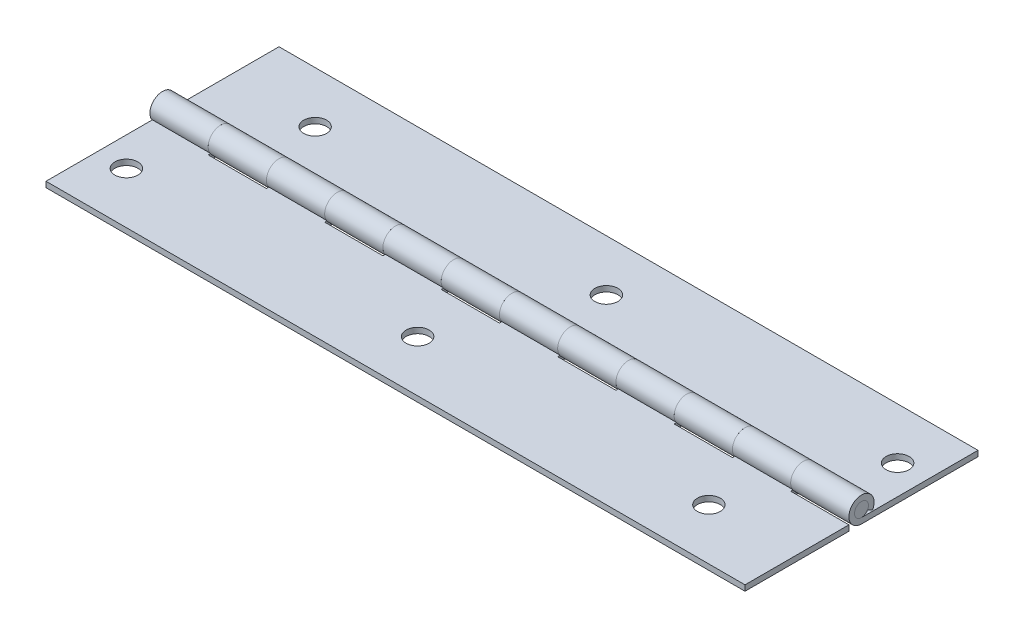
SolidWorks part; units mm, degrees
ref_plane "Front Plane" through (0, 0, 0) normal (0, 0, 1) x (1, 0, 0)
ref_plane "Top Plane" through (0, 0, 0) normal (0, 1, 0) x (1, 0, 0)
ref_plane "Right Plane" through (0, 0, 0) normal (1, 0, 0) x (0, 0, -1)
sketch "Sketch1" plane through (0, 0, 0) normal (0, 1, 0) x (1, 0, 0)
  line L0 (-76.2, 0) -> (76.2, 0) construction
  line L1 (-76.2, -25.4) -> (-76.2, 25.4) construction
  line L2 (-76.2, -25.4) -> (-69.85, -25.4) construction
  line L3 (-69.85, -25.4) -> (-6.35, -25.4) construction
  line L4 (-6.35, -25.4) -> (57.15, -25.4) construction
  line L5 (76.2, -25.4) -> (76.2, -14.224) construction
  line L6 (57.15, -25.4) -> (76.2, -25.4) construction
  line L7 (-76.2, 25.4) -> (-57.15, 25.4) construction
  line L8 (-57.15, 25.4) -> (6.35, 25.4) construction
  line L9 (6.35, 25.4) -> (69.85, 25.4) construction
  line L10 (69.85, 25.4) -> (76.2, 25.4) construction
  line L11 (57.15, -16.7259) -> (57.15, -11.7221) construction
  point P4 (0, 0)
  point P8 (-76.2, 0)
  point P17 (-63.5, 0)
  point P21 (57.15, -14.224)
  dimension "Leaf Height" = 152.4
  dimension "Overall Width" = 50.8
  dimension "Hole to End 1" = 6.35
  dimension "Hole Spacing" = 63.5
  dimension "D3" = 63.5
  dimension "Hole to End 2" = 19.05
  dimension "Hole Center to End" = 11.176
  dimension "D1" = 6.35
  dimension "D2" = 19.05
  dimension "D4" = 63.5
  dimension "D6" = 63.5
  dimension "Knuckle Length" = 12.7
  dimension "Hole Diameter" = 5.0038
sketch "Sketch2" plane through (0, 0, 0) normal (1, 0, 0) x (0, 0, -1)
  line L2 (0, -2.7432) -> (0, -1.524) construction
  line L4 (0, 1.524) -> (0, -1.524) construction
  point P8 (0, 0)
  dimension "Leaf Thickness" = 1.2192
  dimension "Pin Diameter" = 3.048
sketch "Sketch3" plane through (0, 0, 0) normal (1, 0, 0) x (0, 0, -1)
  line L3 (0, 0) -> (-2.7432, -1.524) construction
  line L4 (0, -2.7432) -> (-25.4, -2.7432)
  line L5 (-25.4, -2.7432) -> (-25.4, -1.524)
  line L7 (-25.4, -1.524) -> (0, -1.524)
  line L8 (-25.4, 0) -> (25.4, 0) construction
  line L9 (-1.3322, -0.7401) -> (-2.398, -1.3322)
  line L11 (-2.7432, 0) -> (-2.7432, -1.524) construction
  circle A4 centre (0, 0) radius 1.524 construction
  circle A5 centre (0, 0) radius 2.7432 construction
  arc A8 (-1.3322, -0.7401) -> (0, -1.524) centre (0, 0) cw
  arc A9 (-2.398, -1.3322) -> (0, -2.7432) centre (0, 0) cw
  point P0 (-2.398, -1.3322)
  point P13 (-1.3322, -0.7401)
extrude "Boss-Extrude1" add sketch "Sketch3" along normal mid plane 152.4
sketch "Sketch4" plane through (0, 0, 0) normal (0, 1, 0) x (1, 0, 0)
  line L0 (-76.2, -2.7432) -> (76.2, -2.7432) construction
  line L1 (-76.2, -2.7432) -> (76.2, -2.7432) construction
  line L2 (76.2, 2.7432) -> (-76.2, 2.7432) construction
  line L3 (76.2, 2.7432) -> (-76.2, 2.7432) construction
  line L4 (-63.5, -2.7432) -> (-63.5, 2.7432)
  line L6 (-63.5, 2.7432) -> (-50.8, 2.7432)
  line L7 (-50.8, -2.7432) -> (-63.5, -2.7432)
  line L8 (-50.8, 2.7432) -> (-50.8, -2.7432)
  point P8 (-63.5, 0)
  dimension "D1" = 12.7
extrude "Cut-Extrude1" cut sketch "Sketch4" against normal through all both and the other way through all
pattern_linear "LPattern1" count 6 spacing 25.4 along (1, 0, 0) of "Cut-Extrude1"
sketch "Sketch5" plane through (0, -1.524, 0) normal (0, 1, 0) x (1, 0, 0)
  line L0 (57.15, -14.224) -> (-69.85, -14.224) construction
  line L1 (-6.35, -14.224) -> (-6.35, -25.4) construction
  line L2 (-69.85, -14.224) -> (-69.85, -25.4) construction
  line L3 (76.2, -2.7432) -> (76.2, -25.4) construction
  circle A0 centre (57.15, -14.224) radius 2.5019
  circle A1 centre (-6.35, -14.224) radius 2.5019
  circle A2 centre (-69.85, -14.224) radius 2.5019
extrude "Cut-Extrude2" cut sketch "Sketch5" against normal through all
pattern_circular "CirPattern1" count 2 over 360 about axis through (0, 0, 0) along (0, 1, 0) of bodies 107
sketch "Sketch6" plane through (0, 0, 0) normal (1, 0, 0) x (0, 0, -1)
  circle A0 centre (0, 0) radius 1.524
  dimension "D1" = 3.048
extrude "Boss-Extrude2" add sketch "Sketch6" along normal mid plane 152.4 separate body
sketch "Sketch7" plane through (0, 0, 0) normal (1, 0, 0) x (0, 0, -1)
  line L0 (-1.524, 0) -> (1.524, 0) construction
  line L1 (-25.4, 0) -> (25.4, 0) construction
  line L2 (25.4, -1.524) -> (25.4, -2.7432) construction
  line L3 (25.4, -1.524) -> (25.4, -2.7432) construction
  line L4 (25.4, -2.7432) -> (-25.4, -2.7432) construction
  line L5 (-25.4, -2.7432) -> (-25.4, -1.524)
  point P6 (0, 0)
  point P8 (1.524, 0)
  point P9 (-1.524, 0)
  point P12 (25.4, -1.524)
  point P13 (25.4, -2.7432)
  point P14 (-25.4, -2.7432)
  dimension "D1" = 3.048
  dimension "D2" = 50.8
  dimension "D3" = 1.2192
sketch "Sketch8" plane through (0, 0, 0) normal (0, 1, 0) x (1, 0, 0)
  line L0 (-72.3519, -14.224) -> (-67.3481, -14.224) construction
  line L1 (-8.8519, -14.224) -> (-3.8481, -14.224) construction
  line L2 (54.6481, -14.224) -> (59.6519, -14.224) construction
  line L3 (-69.85, -11.7221) -> (-69.85, -16.7259) construction
  line L4 (-6.35, -11.7221) -> (-6.35, -16.7259) construction
  line L5 (57.15, -11.7221) -> (57.15, -16.7259) construction
  line L6 (-57.15, 16.7259) -> (-57.15, 11.7221) construction
  line L7 (-59.6519, 14.224) -> (-54.6481, 14.224) construction
  line L8 (6.35, 16.7259) -> (6.35, 11.7221) construction
  line L9 (3.8481, 14.224) -> (8.8519, 14.224) construction
  line L10 (69.85, 16.7259) -> (69.85, 11.7221) construction
  line L11 (67.3481, 14.224) -> (72.3519, 14.224) construction
  line L12 (69.85, 14.224) -> (71.6191, 15.9931) construction
  circle A1 centre (-69.85, -14.224) radius 2.5019 construction
  circle A2 centre (-6.35, -14.224) radius 2.5019 construction
  circle A3 centre (57.15, -14.224) radius 2.5019 construction
  circle A4 centre (-57.15, 14.224) radius 2.5019 construction
  circle A5 centre (6.35, 14.224) radius 2.5019 construction
  circle A6 centre (69.85, 14.224) radius 2.5019 construction
  circle A7 centre (69.85, 14.224) radius 2.5019 construction
  point P2 (-76.2, 0)
  point P7 (-69.85, -14.224)
  point P13 (-6.35, -14.224)
  point P19 (57.15, -14.224)
  point P25 (-76.2, 25.4)
  point P26 (76.2, 25.4)
  point P28 (-76.2, -25.4)
  point P30 (76.2, -25.4)
  point P32 (-72.3519, -14.224)
  point P33 (-69.85, -11.7221)
  point P34 (-67.3481, -14.224)
  point P35 (-69.85, -16.7259)
  point P36 (-6.35, -16.7259)
  point P37 (-8.8519, -14.224)
  point P38 (-6.35, -11.7221)
  point P39 (-3.8481, -14.224)
  point P40 (59.6519, -14.224)
  point P41 (57.15, -16.7259)
  point P42 (54.6481, -14.224)
  point P43 (57.15, -11.7221)
  point P66 (-6.35, -25.4)
  point P67 (57.15, -25.4)
  point P69 (-69.85, -25.4)
  point P71 (-57.15, 25.4)
  point P73 (-57.15, 14.224)
  point P75 (6.35, 14.224)
  point P76 (69.85, 14.224)
  point P77 (69.85, 25.4)
  point P78 (6.35, 25.4)
  point P82 (-57.15, 16.7259)
  point P83 (-59.6519, 14.224)
  point P84 (-57.15, 11.7221)
  point P85 (-54.6481, 14.224)
  point P86 (6.35, 11.7221)
  point P87 (3.8481, 14.224)
  point P88 (6.35, 16.7259)
  point P89 (8.8519, 14.224)
  point P90 (69.85, 11.7221)
  point P91 (67.3481, 14.224)
  point P92 (69.85, 16.7259)
  point P93 (72.3519, 14.224)
  point P97 (71.6191, 15.9931)
  dimension "D1" = 45
equation "\"D3@Sketch1\"=\"Hole Spacing@Sketch1\""
equation "\"D1@Sketch1\"=\"Hole to End 1@Sketch1\""
equation "\"D2@Sketch1\"=\"Hole to End 2@Sketch1\""
equation "\"D4@Sketch1\"=\"Hole Spacing@Sketch1\""
equation "\"D6@Sketch1\"=\"D4@Sketch1\""
equation "\"D1@Boss-Extrude1\"=\"Leaf Height@Sketch1\""
equation "\"D1@Sketch4\"=\"Knuckle Length@Sketch1\""
equation "\"D3@LPattern1\"=\"Knuckle Length@Sketch1\"*2"
equation "\"D1@Sketch6\"=\"Pin Diameter@Sketch2\""
equation "\"D1@Boss-Extrude2\"=\"Leaf Height@Sketch1\""
equation "\"D1@Sketch7\"=\"Pin Diameter@Sketch2\""
equation "\"D2@Sketch7\"=\"Overall Width@Sketch1\""
equation "\"D3@Sketch7\"=\"Leaf Thickness@Sketch2\""
